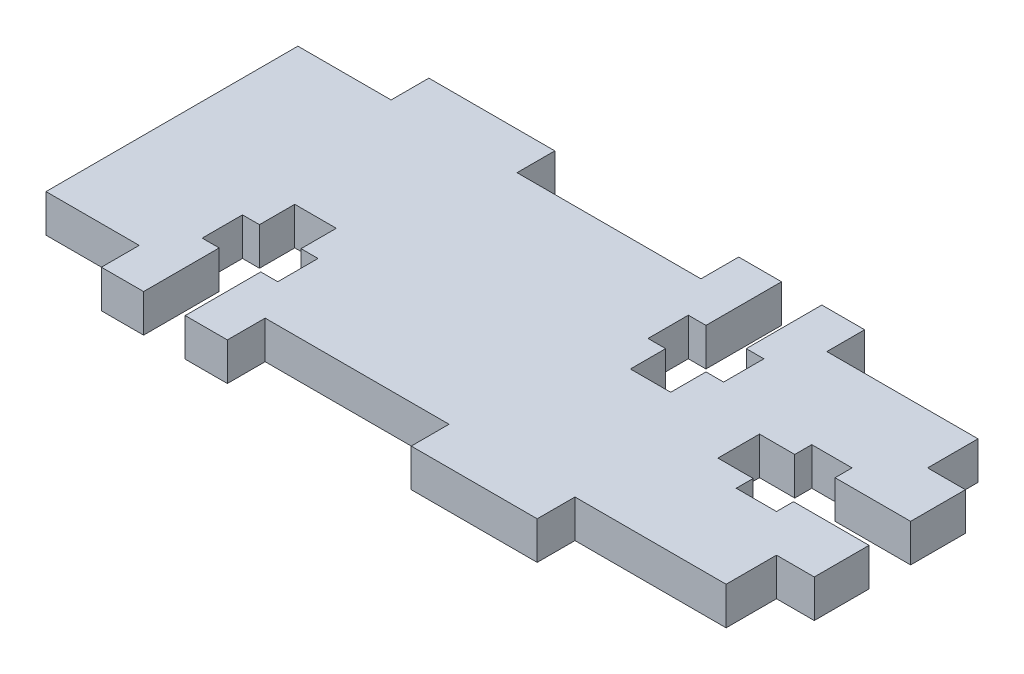
SolidWorks part; units mm, degrees
material "Thornel Mat VMA"
ref_plane "前视基准面" through (0, 0, 0) normal (0, 0, 1) x (1, 0, 0)
ref_plane "上视基准面" through (0, 0, 0) normal (0, 1, 0) x (1, 0, 0)
ref_plane "右视基准面" through (0, 0, 0) normal (1, 0, 0) x (0, 0, -1)
other "Configuration Table"
sketch "草图1" plane through (0, 0, 0) normal (0, 1, 0) x (1, 0, 0)
  line L0 (0, 7.8453) -> (0, -6) construction
  line L1 (-17, 10) -> (17, 10)
  line L2 (-17, 10) -> (-17, -10)
  line L3 (-17, -10) -> (17, -10)
  line L4 (17, 10) -> (17, -10)
  line L5 (-17, 10) -> (17, -10) construction
  line L6 (-17, -10) -> (17, 10) construction
  line L7 (17, 6) -> (20, 6)
  line L8 (17, 6) -> (17, -6)
  line L9 (17, -6) -> (20, -6)
  line L10 (20, 6) -> (20, -6)
  line L11 (-17, -6) -> (-20, -6)
  line L12 (-20, 6) -> (-20, -6)
  line L13 (-17, 6) -> (-20, 6)
  line L14 (-17, 6) -> (-17, -6)
  line L15 (-4.2168, 0) -> (3.1019, 0) construction
  line L16 (-5, 10) -> (5, 10)
  line L17 (-5, 10) -> (-5, 13)
  line L18 (-5, 13) -> (5, 13)
  line L19 (5, 10) -> (5, 13)
  line L20 (-5, -13) -> (5, -13)
  line L21 (5, -10) -> (5, -13)
  line L22 (-5, -10) -> (5, -10)
  line L23 (-5, -10) -> (-5, -13)
  point P0 (0, 0)
  point P10 (20, 0)
  point P21 (0, 13)
  dimension "D1" = 20
  dimension "D2" = 34
  dimension "D3" = 3
  dimension "D4" = 12
  dimension "D5" = 3
  dimension "D6" = 10
extrude "凸台-拉伸1" add sketch "草图1" along normal blind 3 contours L4 L1 L2 L3 | L1 L19 L18 L17 | L10 L7 L4 L9 | L3 L23 L20 L21
sketch "草图2" plane through (0, 3, 0) normal (0, 1, 0) x (1, 0, 0)
  line L0 (20, 6) -> (20, -6) construction
  line L1 (8, 1.65) -> (32, 1.65)
  line L2 (8, 1.65) -> (8, -1.65)
  line L3 (8, -1.65) -> (32, -1.65)
  line L4 (32, 1.65) -> (32, -1.65)
  line L5 (8, 1.65) -> (32, -1.65) construction
  line L6 (8, -1.65) -> (32, 1.65) construction
  line L7 (20, 0) -> (12.4, 0) construction
  line L9 (10.8, 3) -> (14, 3)
  line L10 (10.8, 3) -> (10.8, -3)
  line L11 (10.8, -3) -> (14, -3)
  line L12 (14, 3) -> (14, -3)
  line L13 (10.8, 3) -> (14, -3) construction
  line L14 (10.8, -3) -> (14, 3) construction
  point P0 (20, 0)
  line M13 (20, -6) -> (20, 6)
  dimension "D1" = 3.3
  dimension "D2" = 24
  dimension "D3" = 3.2
  dimension "D4" = 6
  dimension "D5" = 6
extrude "切除-拉伸1" cut sketch "草图2" against normal blind 3 contours L10 L1 L2 L3 | L12 L9 L10 L1 | L12 L1 L10 L3 | L12 L3 L10 L11 | L1 L12 L3 M13
sketch "草图4" plane through (0, 3, 0) normal (0, 1, 0) x (1, 0, 0)
  line L0 (-17, 10) -> (-5, 10) construction
  line L1 (-17, -10) -> (-37, -10)
  line L2 (-17, -10) -> (-17, 10)
  line L3 (-17, 10) -> (-37, 10)
  line L4 (-37, -10) -> (-37, 10)
  line L5 (-5, 10) -> (-5, 13) construction
  line L6 (-29.6, 10) -> (-19.6, 10)
  line L7 (-29.6, 10) -> (-29.6, 13)
  line L8 (-29.6, 13) -> (-19.6, 13)
  line L9 (-19.6, 10) -> (-19.6, 13)
  line L10 (-5.4018, 0) -> (3.52, 0) construction
  line L11 (-29.6, -13) -> (-19.6, -13)
  line L12 (-19.6, -10) -> (-19.6, -13)
  line L13 (-29.6, -10) -> (-19.6, -10)
  line L14 (-29.6, -10) -> (-29.6, -13)
  line M19 (-17, 10) -> (-17, -10)
  dimension "D1" = 20
  dimension "D2" = 3
  dimension "D3" = 10
  dimension "D4" = 14.6
extrude "凸台-拉伸2" add sketch "草图4" against normal blind 3 contours L4 L1 L3 M19 | L3 L9 L8 L7 | L1 L14 L11 L12
sketch "草图5" plane through (0, 3, 0) normal (0, 1, 0) x (1, 0, 0)
  line L0 (-5, 13) -> (5, 13) construction
  line L1 (-1.6, 25) -> (1.6, 25)
  line L2 (-1.6, 25) -> (-1.6, 1)
  line L3 (-1.6, 1) -> (1.6, 1)
  line L4 (1.6, 25) -> (1.6, 1)
  line L5 (-1.6, 25) -> (1.6, 1) construction
  line L6 (-1.6, 1) -> (1.6, 25) construction
  line L7 (0, 13) -> (0, 5.4) construction
  line L8 (-29.6, -13) -> (-19.6, -13) construction
  line L9 (-3, 7) -> (3, 7)
  line L10 (-3, 7) -> (-3, 3.8)
  line L11 (-3, 3.8) -> (3, 3.8)
  line L12 (3, 7) -> (3, 3.8)
  line L13 (-3, 7) -> (3, 3.8) construction
  line L14 (-3, 3.8) -> (3, 7) construction
  line L15 (-26.25, -1) -> (-22.95, -1)
  line L16 (-26.25, -1) -> (-26.25, -25)
  line L17 (-26.25, -25) -> (-22.95, -25)
  line L18 (-22.95, -1) -> (-22.95, -25)
  line L19 (-26.25, -1) -> (-22.95, -25) construction
  line L20 (-26.25, -25) -> (-22.95, -1) construction
  line L21 (-24.6, -13) -> (-24.6, -5.4) construction
  line L23 (-27.6, -3.8) -> (-21.6, -3.8)
  line L24 (-27.6, -3.8) -> (-27.6, -7)
  line L25 (-27.6, -7) -> (-21.6, -7)
  line L26 (-21.6, -3.8) -> (-21.6, -7)
  line L27 (-27.6, -3.8) -> (-21.6, -7) construction
  line L28 (-27.6, -7) -> (-21.6, -3.8) construction
  point P0 (0, 13)
  point P14 (-24.6, -13)
  point P27 (-24.6, -13)
  line M12 (5, 13) -> (-5, 13)
  line M22 (-29.6, -13) -> (-19.6, -13)
  dimension "D1" = 24
  dimension "D2" = 3.2
  dimension "D3" = 3.2
  dimension "D4" = 6
  dimension "D5" = 6
  dimension "D6" = 24
  dimension "D7" = 3.3
  dimension "D8" = 3.2
  dimension "D9" = 6
  dimension "D10" = 6
extrude "切除-拉伸2" cut sketch "草图5" against normal blind 3 contours L11 L2 L3 L4 | L10 L11 L2 L9 | L2 L9 L4 M12 | L2 L11 L4 L9 | L12 L9 L4 L11 | L24 L25 L16 L23 | L16 L23 L18 L15 | L26 L23 L18 L25 | L16 L25 L18 L23 | L25 L16 L18 M22
